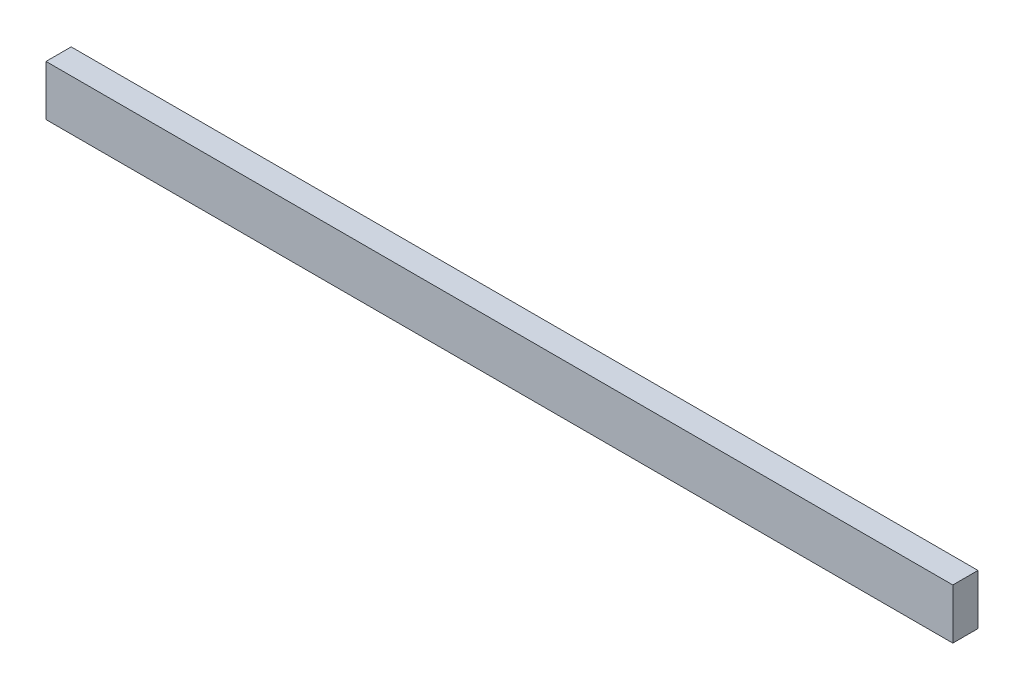
SolidWorks part; units mm, degrees
ref_plane "Front Plane" through (0, 0, 0) normal (0, 0, 1) x (1, 0, 0)
ref_plane "Top Plane" through (0, 0, 0) normal (0, 1, 0) x (1, 0, 0)
ref_plane "Right Plane" through (0, 0, 0) normal (1, 0, 0) x (0, 0, -1)
sketch "Sketch1" plane through (0, 0, 0) normal (1, 0, 0) x (0, 0, -1)
  line L1 (-15, -30) -> (15, -30)
  line L2 (-15, -30) -> (-15, 30)
  line L3 (-15, 30) -> (15, 30)
  line L4 (15, -30) -> (15, 30)
  line L5 (-15, -30) -> (15, 30) construction
  line L6 (-15, 30) -> (15, -30) construction
  point P0 (0, 0)
  dimension "D1" = 30
  dimension "D2" = 60
extrude "Boss-Extrude1" add sketch "Sketch1" along normal blind 1080
